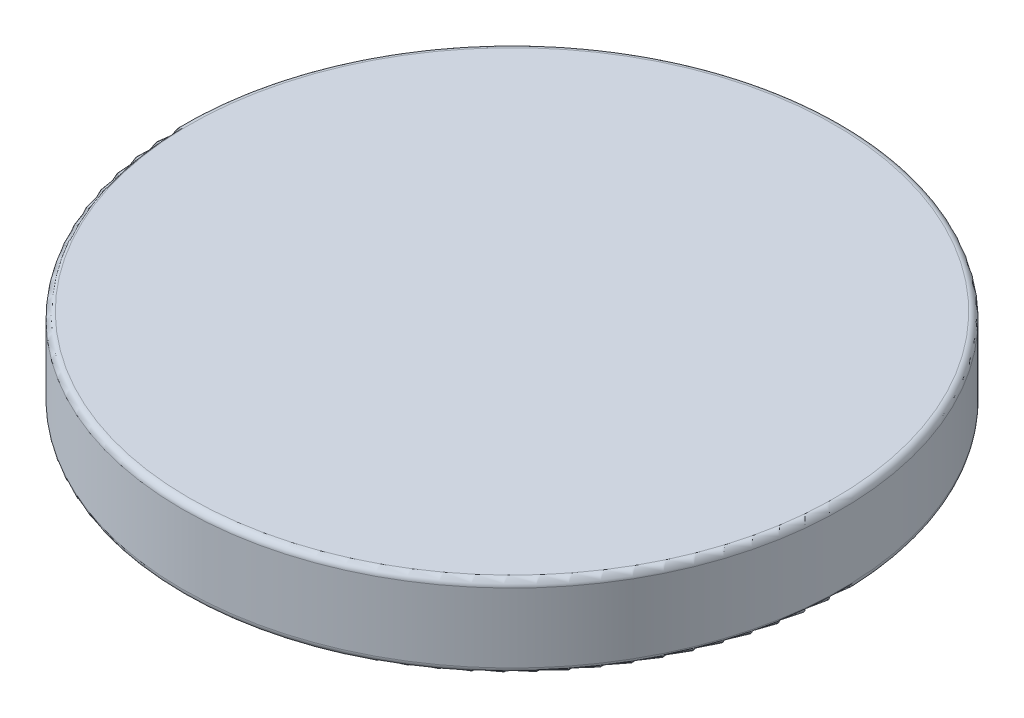
SolidWorks part; units mm, degrees
ref_plane "Front Plane" through (0, 0, 0) normal (0, 0, 1) x (1, 0, 0)
ref_plane "Top Plane" through (0, 0, 0) normal (0, 1, 0) x (1, 0, 0)
ref_plane "Right Plane" through (0, 0, 0) normal (1, 0, 0) x (0, 0, -1)
sketch "Sketch1" plane through (0, 0, 0) normal (0, 1, 0) x (1, 0, 0)
  circle A0 centre (0, 0) radius 12.7
extrude "Boss-Extrude1" add sketch "Sketch1" along normal blind 3.175
fillet "Fillet1" radius 0.254 2 edges at (0, 3.175, 12.7) (0, 0, 12.7)
